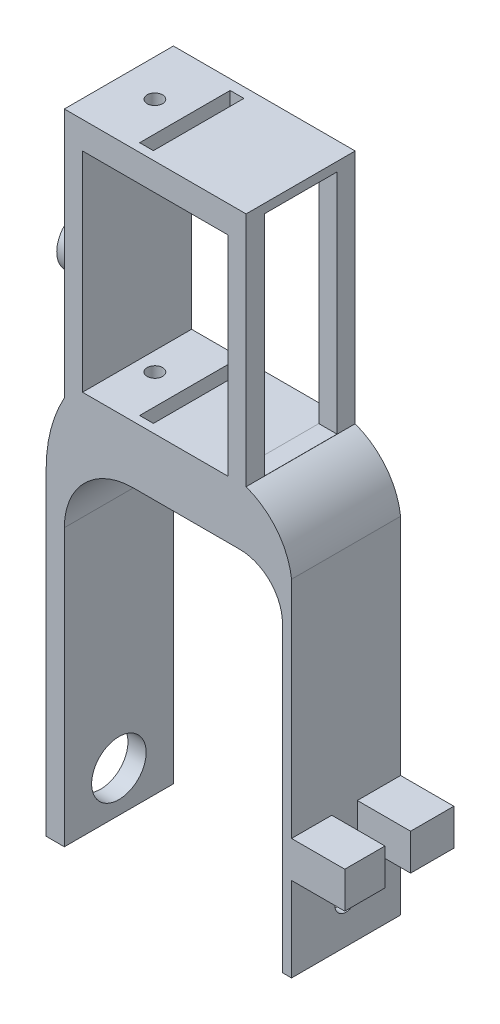
SolidWorks part; units mm, degrees
ref_plane "Front Plane" through (0, 0, 0) normal (0, 0, 1) x (1, 0, 0)
ref_plane "Top Plane" through (0, 0, 0) normal (0, 1, 0) x (1, 0, 0)
ref_plane "Right Plane" through (0, 0, 0) normal (1, 0, 0) x (0, 0, -1)
sketch "Sketch1" plane through (0, 0, 0) normal (0, 0, 1) x (1, 0, 0)
  line L0 (-1000, 0) -> (49000, 0) construction
  line L1 (0, -1000) -> (0, 49000) construction
  line L2 (-13.2583, -23.243) -> (-8.2583, -23.243)
  line L3 (-8.2583, -23.243) -> (-8.2583, 52.784)
  line L5 (51.7417, 60.019) -> (51.7417, -23.243)
  line L6 (51.7417, -23.243) -> (54.2417, -23.243)
  line L7 (54.2417, -23.243) -> (54.2417, 0)
  line L8 (54.2417, 0) -> (68.8861, 0)
  line L9 (68.8861, 0) -> (68.8861, 10)
  line L10 (68.8861, 10) -> (54.2417, 10)
  line L11 (54.2417, 10) -> (54.2417, 71.757)
  line L12 (41.7417, 87.5424) -> (41.7417, 152.5424)
  line L13 (41.7417, 152.5424) -> (-8.2583, 152.5424)
  line L15 (-13.2583, -23.243) -> (-13.2583, 64.3414)
  line L16 (-8.2583, 152.5424) -> (-8.2583, 83.6916)
  line L17 (10.7147, 71.757) -> (40.0037, 71.757)
  arc A0 (-8.2583, 52.784) -> (10.7147, 71.757) centre (10.7147, 52.784) cw
  arc A3 (-13.2583, 64.3414) -> (-8.2583, 83.6916) centre (26.6847, 64.3414) cw
  arc A4 (40.0037, 71.757) -> (51.7417, 60.019) centre (40.0037, 60.019) cw
  arc A5 (54.2417, 71.757) -> (41.7417, 87.5424) centre (35.1994, 69.5199) ccw
  point P27 (-2.7012, 66.1999)
  point P28 (54.2417, 0)
  dimension "D4" = 8.2583
  dimension "D5" = 15.7854
  dimension "D1" = 2.5
  dimension "D2" = 5
  dimension "D3" = 50
  dimension "D6" = 10
  dimension "D7" = 60
  dimension "D8" = 65
  dimension "D9" = 95
  dimension "D10" = 13.416
extrude "Boss-Extrude1" add sketch "Sketch1" against normal blind 30
sketch "Sketch8" plane through (41.7417, 0, 0) normal (1, 0, 0) x (0, 0, -1)
  line L4 (0, 152.5424) -> (0, 87.5424)
  line L5 (0, 87.5424) -> (30, 87.5424)
  line L6 (30, 87.5424) -> (30, 152.5424)
  line L7 (30, 152.5424) -> (0, 152.5424)
  line L8 (0, 152.5424) -> (0, 87.5424)
  line L10 (30, 87.5424) -> (30, 152.5424)
  line L11 (30, 152.5424) -> (0, 152.5424)
  line L12 (5, 87.5831) -> (25, 87.5831)
  line L13 (25, 87.5831) -> (25, 150.0424)
  line L14 (25, 150.0424) -> (5, 150.0424)
  line L15 (5, 150.0424) -> (5, 87.5831)
  line L20 (0, 87.5424) -> (30, 87.5424)
  dimension "D2" = 2.5
  dimension "D3" = 5
  dimension "D4" = 5
  dimension "D1" = 0
extrude "Cut-Extrude10" cut sketch "Sketch8" against normal blind 10
sketch "Sketch9" plane through (0, 0, 0) normal (0, 0, 1) x (1, 0, 0)
  line L0 (-3.2583, 145.0424) -> (-3.2583, 87.5572)
  line L1 (-3.2583, 87.5572) -> (36.7417, 87.5572)
  line L2 (-958.2583, 87.5424) -> (49041.7417, 87.5424) construction
  line L14 (-3.2583, 145.0424) -> (36.7417, 145.0424)
  line L15 (36.7417, 145.0424) -> (36.7417, 87.5572)
extrude "Cut-Extrude11" cut sketch "Sketch9" against normal through all
sketch "Sketch10" plane through (0, 152.5424, 0) normal (0, 1, 0) x (1, 0, 0)
  line L0 (10.137, 27.2142) -> (10.137, 2.3164)
  line L1 (10.137, 2.3164) -> (13.9244, 2.3164)
  line L2 (13.9244, 2.3164) -> (13.9244, 27.2142)
  line L3 (13.9244, 27.2142) -> (10.137, 27.2142)
extrude "Cut-Extrude12" cut sketch "Sketch10" against normal through all
sketch "Sketch11" plane through (-8.2583, 0, 0) normal (-1, 0, 0) x (0, 0, 1)
  line L0 (-30, 152.5424) -> (0, 152.5424) construction
  circle A0 centre (-15.4042, 109.5424) radius 7.5
  dimension "D1" = 15
  dimension "D2" = 43
extrude "Boss-Extrude3" add sketch "Sketch11" along normal blind 10
sketch "Sketch13" plane through (68.8861, 0, 0) normal (1, 0, 0) x (0, 0, -1)
  line L0 (11.0597, 10) -> (11.0597, 0)
  line L1 (30, 10) -> (0, 10) construction
  line L2 (30, 0) -> (0, 0) construction
  line L3 (11.0597, 0) -> (18.0991, 0)
  line L4 (18.0991, 0) -> (18.0991, 10)
  line L5 (18.0991, 10) -> (11.0597, 10)
extrude "Cut-Extrude13" cut sketch "Sketch13" against normal up to surface (14.6444 mm away) up to face at (54.2417, 40.8785, -15)
sketch "Sketch14" plane through (54.2417, 0, 0) normal (1, 0, 0) x (0, 0, -1)
  line L0 (15, -999.1766) -> (15, 49000.8234) construction
  line L4 (0, 0) -> (0, -23.243)
  line L5 (0, -23.243) -> (30, -23.243)
  line L6 (30, -23.243) -> (30, 0)
  line L7 (30, 0) -> (18.0991, 0)
  line L8 (0, 0) -> (0, -23.243)
  line L9 (0, -23.243) -> (30, -23.243)
  line L10 (30, -23.243) -> (30, 0)
  line L11 (30, 0) -> (18.0991, 0)
  line L21 (0, 71.757) -> (0, 10)
  line L22 (0, 71.757) -> (0, 10)
  line L23 (0, 10) -> (11.0597, 10)
  line L24 (0, 10) -> (11.0597, 10)
  line L25 (11.0597, 10) -> (11.0597, 0)
  line L26 (11.0597, 10) -> (11.0597, 0)
  line L27 (11.0597, 0) -> (0, 0)
  line L28 (11.0597, 0) -> (0, 0)
  line L29 (18.0991, 0) -> (18.0991, 10)
  line L30 (18.0991, 0) -> (18.0991, 10)
  line L31 (18.0991, 10) -> (30, 10)
  line L32 (18.0991, 10) -> (30, 10)
  line L33 (30, 10) -> (30, 71.757)
  line L34 (30, 10) -> (30, 71.757)
  line L35 (30, 71.757) -> (0, 71.757)
  line L37 (30, 71.757) -> (0, 71.757)
  circle A0 centre (15, -12) radius 3.05
  point P2 (15, -12)
  dimension "D2" = 6.1
  dimension "D3" = 12
  dimension "D1" = 0
extrude "Cut-Extrude14" cut sketch "Sketch14" against normal blind 10 contours A0 L0 | L0 A0
sketch "Sketch15" plane through (-13.2583, 0, 0) normal (-1, 0, 0) x (0, 0, 1)
  line L4 (0, -23.243) -> (0, 64.3414)
  line L5 (0, 64.3414) -> (-30, 64.3414)
  line L6 (-30, 64.3414) -> (-30, -23.243)
  line L7 (-30, -23.243) -> (0, -23.243)
  line L8 (0, -23.243) -> (0, 64.3414)
  line L9 (0, 64.3414) -> (-30, 64.3414)
  line L10 (-30, 64.3414) -> (-30, -23.243)
  line L11 (-30, -23.243) -> (0, -23.243)
  circle A0 centre (-15, -12) radius 3.05 construction
  circle A1 centre (-15, -12) radius 3.05
  circle A2 centre (-15, -12) radius 7.5
  dimension "D2" = 15
  dimension "D1" = 0
extrude "Cut-Extrude15" cut sketch "Sketch15" against normal blind 10 contours A2 A1 | A1
sketch "Sketch16" plane through (0, 152.5424, 0) normal (0, 1, 0) x (1, 0, 0)
  line L4 (-8.2583, 0) -> (41.7417, 0)
  line L5 (41.7417, 0) -> (41.7417, 30)
  line L6 (41.7417, 30) -> (-8.2583, 30)
  line L7 (-8.2583, 30) -> (-8.2583, 0)
  line L8 (-8.2583, 0) -> (41.7417, 0)
  line L9 (41.7417, 0) -> (41.7417, 30)
  line L10 (41.7417, 30) -> (-8.2583, 30)
  line L11 (-8.2583, 30) -> (-8.2583, 0)
  circle A0 centre (1.8736, 14.7653) radius 2.125
  dimension "D2" = 4.25
  dimension "D1" = 0
extrude "Cut-Extrude16" cut sketch "Sketch16" against normal through all contours A0
